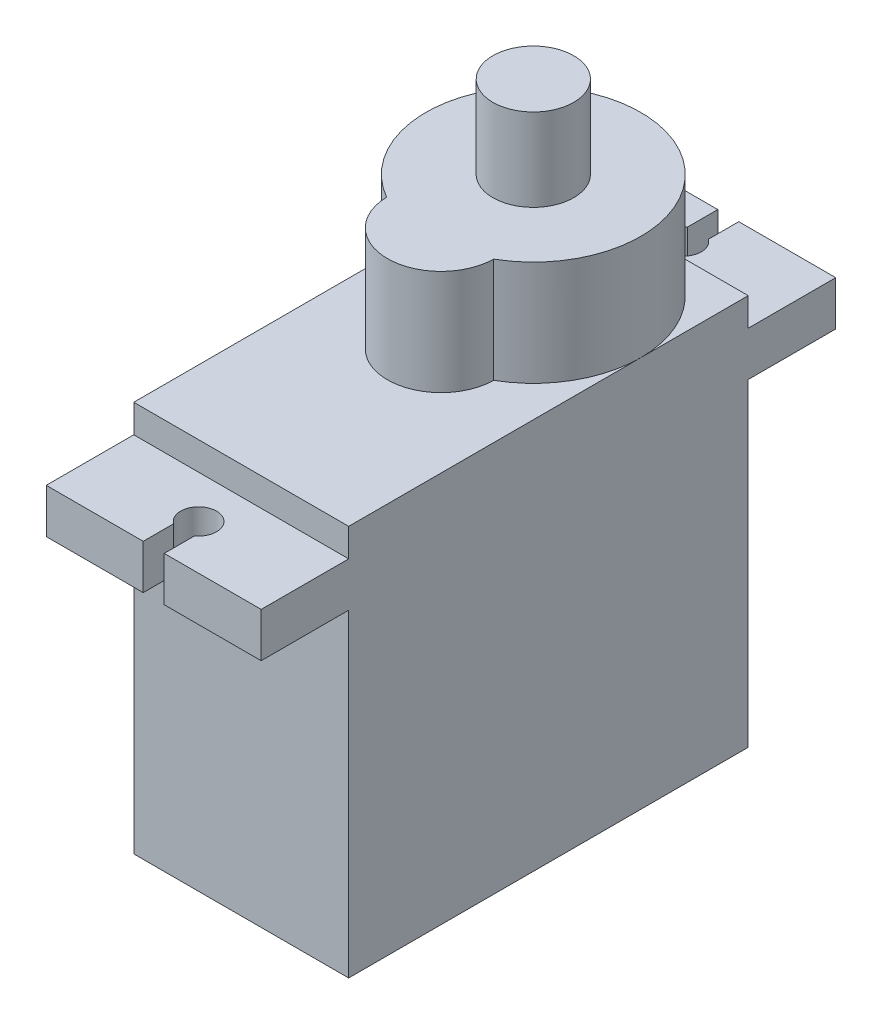
SolidWorks part; units mm, degrees
ref_plane "Front Plane" through (0, 0, 0) normal (0, 0, 1) x (1, 0, 0)
ref_plane "Top Plane" through (0, 0, 0) normal (0, 1, 0) x (1, 0, 0)
ref_plane "Right Plane" through (0, 0, 0) normal (1, 0, 0) x (0, 0, -1)
sketch "Sketch1" plane through (0, 0, 0) normal (0, 1, 0) x (1, 0, 0)
  line L1 (-6.14, 11.415) -> (6.14, 11.415)
  line L2 (-6.14, 11.415) -> (-6.14, -11.415)
  line L3 (-6.14, -11.415) -> (6.14, -11.415)
  line L4 (6.14, 11.415) -> (6.14, -11.415)
  line L5 (-6.14, 11.415) -> (6.14, -11.415) construction
  line L6 (-6.14, -11.415) -> (6.14, 11.415) construction
  point P0 (0, 0)
  dimension "D1" = 12.28
  dimension "D2" = 22.83
extrude "Boss-Extrude1" add sketch "Sketch1" along normal blind 22.35
ref_plane "Plane1" through (0, 18.2, 0) normal (0, -1, 0) x (-1, 0, 0)
sketch "Sketch2" plane through (0, 18.2, 0) normal (0, -1, 0) x (-1, 0, 0)
  line L0 (6.14, 11.415) -> (6.14, 16.415)
  line L1 (6.14, 16.415) -> (0.6, 16.415)
  line L2 (-6.14, 16.415) -> (-6.14, 11.415)
  line L3 (6.14, -11.415) -> (6.14, -16.415)
  line L4 (-6.14, 11.415) -> (-6.14, -11.415)
  line L5 (6.14, 11.415) -> (-6.14, 11.415)
  line L6 (6.14, -11.415) -> (6.14, 11.415)
  line L7 (-6.14, -11.415) -> (6.14, -11.415)
  line L8 (-6.14, 11.415) -> (-6.14, -11.415) construction
  line L9 (6.14, 11.415) -> (-6.14, 11.415)
  line L10 (6.14, -11.415) -> (6.14, 11.415) construction
  line L11 (-6.14, -11.415) -> (6.14, -11.415)
  line L12 (6.14, -16.415) -> (0.6, -16.415)
  line L13 (-6.14, -16.415) -> (-6.14, -11.415)
  line L14 (0, 13.85) -> (0, -13.85) construction
  line L15 (0.6, 14.681) -> (0.6, 13.85) construction
  line L16 (0, -13.85) -> (-0.6, -13.85) construction
  line L17 (0.6, -14.681) -> (0.6, -16.415)
  line L18 (0.6, -16.415) -> (-0.6, -16.415) construction
  line L19 (-0.6, -14.681) -> (-0.6, -16.415)
  line L20 (0.6, -13.85) -> (-0.6, -16.415) construction
  line L21 (0.6, -16.415) -> (-0.6, -13.85) construction
  line L22 (0.6, 16.415) -> (-0.6, 16.415) construction
  line L23 (0.6, 16.415) -> (0.6, 14.681)
  line L24 (0.6, 13.85) -> (0, 13.85) construction
  line L25 (-0.6, 16.415) -> (-0.6, 14.681)
  line L26 (0.6, 16.415) -> (-0.6, 13.85) construction
  line L27 (0.124, 14.8675) -> (-0.6, 16.415) construction
  line L28 (0.6, 13.85) -> (0.124, 14.8675) construction
  line L29 (0, 13.85) -> (-0.6, 13.85) construction
  line L30 (-0.6, 14.681) -> (-0.6, 13.85) construction
  line L31 (0.6, 16.415) -> (-0.6, 16.415) construction
  line L32 (-0.6, 16.415) -> (-6.14, 16.415)
  line L33 (0.6, -16.415) -> (-0.6, -16.415) construction
  line L34 (-0.6, -16.415) -> (-6.14, -16.415)
  line L35 (0.6, -13.85) -> (0.6, -14.681) construction
  line L36 (0.6, -13.85) -> (0, -13.85) construction
  line L37 (-0.6, -13.85) -> (-0.6, -14.681) construction
  arc A0 (-0.6, 14.681) -> (0.6, 14.681) centre (0, 13.85) ccw
  arc A1 (0.6, -14.681) -> (-0.6, -14.681) centre (0, -13.85) ccw
  arc A2 (0.124, -14.8675) -> (0.6, -14.681) centre (0, -13.85) ccw construction
  arc A3 (-0.124, -14.8675) -> (0.124, -14.8675) centre (0, -13.85) ccw construction
  arc A4 (-0.6, -14.681) -> (-0.124, -14.8675) centre (0, -13.85) ccw construction
  arc A5 (0.6, 14.681) -> (0.124, 14.8675) centre (0, 13.85) ccw construction
  arc A6 (0.124, 14.8675) -> (-0.124, 14.8675) centre (0, 13.85) ccw construction
  arc A7 (-0.124, 14.8675) -> (-0.6, 14.681) centre (0, 13.85) ccw construction
  point P15 (0, 0)
  point P16 (0, -12.825)
  point P17 (0, 12.825)
  point P18 (0, -15.1325)
  point P25 (0, 15.1325)
  point P30 (0, 0)
  point P31 (0, 0)
  point P32 (0, 0)
  point P33 (-0.6, -13.4004)
  dimension "D4" = 2.05
  dimension "D2" = 5
  dimension "D3" = 27.7
  dimension "D5" = 32.83
  dimension "D6" = 25.65
  dimension "D7" = 1.2
  dimension "D1" = 0
extrude "Boss-Extrude2" add sketch "Sketch2" against normal blind 2.54
sketch "Sketch3" plane through (0, 22.35, 0) normal (0, 1, 0) x (1, 0, 0)
  line L0 (6.14, 11.415) -> (-6.14, 11.415) construction
  line L1 (-6.14, 11.415) -> (-6.14, -11.415) construction
  line L2 (-6.14, 11.415) -> (-6.14, -11.415) construction
  arc A0 (-3.0596, -0.0484) -> (3.0596, -0.0484) centre (0, 0) ccw
  arc A1 (3.0596, -0.0484) -> (-3.0596, -0.0484) centre (0, 5.275) ccw
  arc A2 (3.0596, -0.0484) -> (-3.0596, -0.0484) centre (0, 0) ccw construction
  arc A3 (-3.0596, -0.0484) -> (3.0596, -0.0484) centre (0, 5.275) ccw construction
  point P5 (0, -3.06)
  point P6 (0, 11.0879)
  point P7 (0, 11.415)
  point P8 (0, 0)
  point P11 (0, 5.9162)
  dimension "D1" = 6.12
extrude "Boss-Extrude3" add sketch "Sketch3" along normal blind 6
ref_plane "Plane2" through (0, 33.07, 0) normal (0, 1, 0) x (1, 0, 0)
sketch "Sketch4" plane through (0, 33.07, 0) normal (0, 1, 0) x (1, 0, 0)
  circle A0 centre (0, 5.275) radius 2.31
  dimension "D1" = 4.62
extrude "Boss-Extrude4" add sketch "Sketch4" against normal up to next separate body
